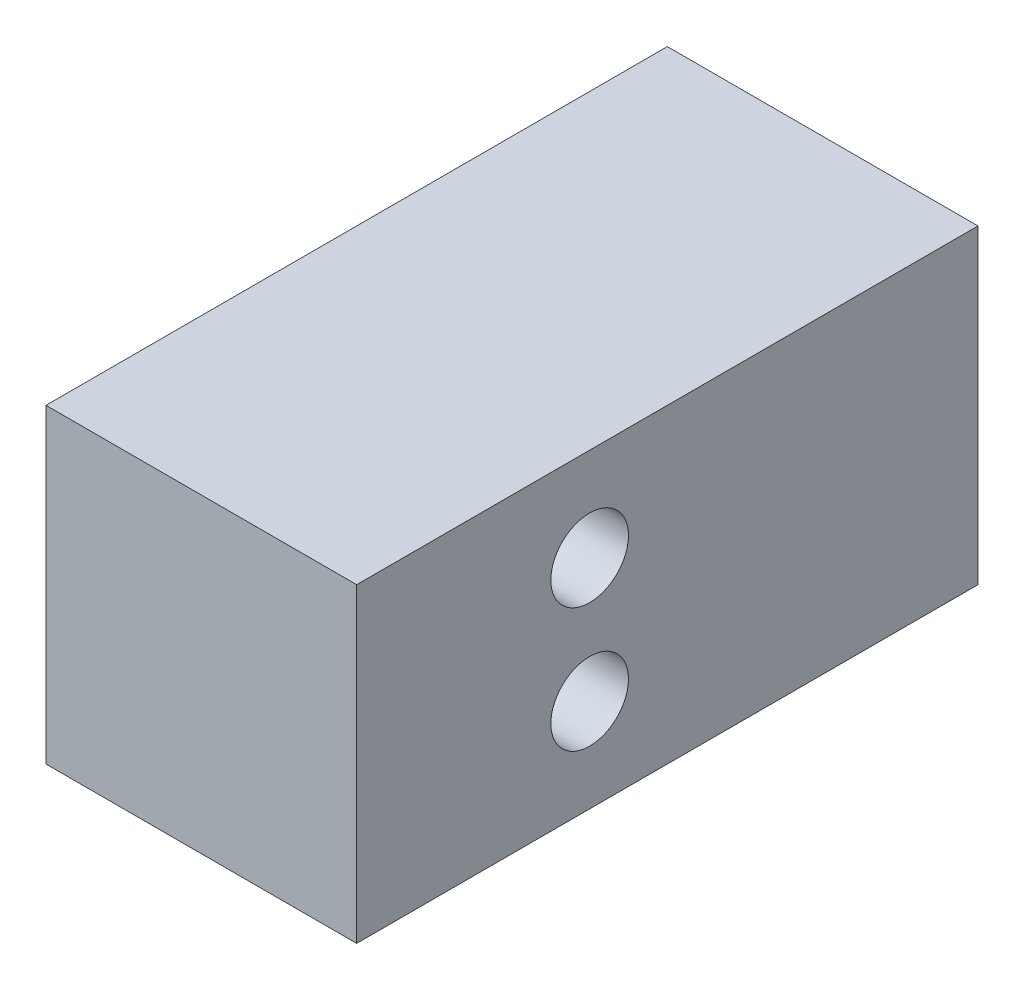
SolidWorks part; units mm, degrees
ref_plane "Front Plane" through (0, 0, 0) normal (0, 0, 1) x (1, 0, 0)
ref_plane "Top Plane" through (0, 0, 0) normal (0, 1, 0) x (1, 0, 0)
ref_plane "Right Plane" through (0, 0, 0) normal (1, 0, 0) x (0, 0, -1)
sketch "Sketch1" plane through (0, 0, 0) normal (0, 0, 1) x (1, 0, 0)
  line L1 (-5, 5) -> (5, 5)
  line L2 (-5, 5) -> (-5, -5)
  line L3 (-5, -5) -> (5, -5)
  line L4 (5, 5) -> (5, -5)
  line L5 (-5, 5) -> (5, -5) construction
  line L6 (-5, -5) -> (5, 5) construction
  point P0 (0, 0)
  dimension "D1" = 10
  dimension "D2" = 10
extrude "Boss-Extrude1" add sketch "Sketch1" against normal blind 20
sketch "Sketch3" plane through (5, 0, 0) normal (1, 0, 0) x (0, 0, -1)
  line L0 (0, -5) -> (0, 5) construction
  line L1 (20, 5) -> (0, 5) construction
  circle A0 centre (7.5, 2) radius 1.25
  dimension "D1" = 2.5
  dimension "D2" = 7.5
  dimension "D3" = 3
extrude "Cut-Extrude6" cut sketch "Sketch3" against normal blind 10
mirror "Mirror1" about plane through (0, 0, 0) normal (0, 1, 0) of "Cut-Extrude6"
